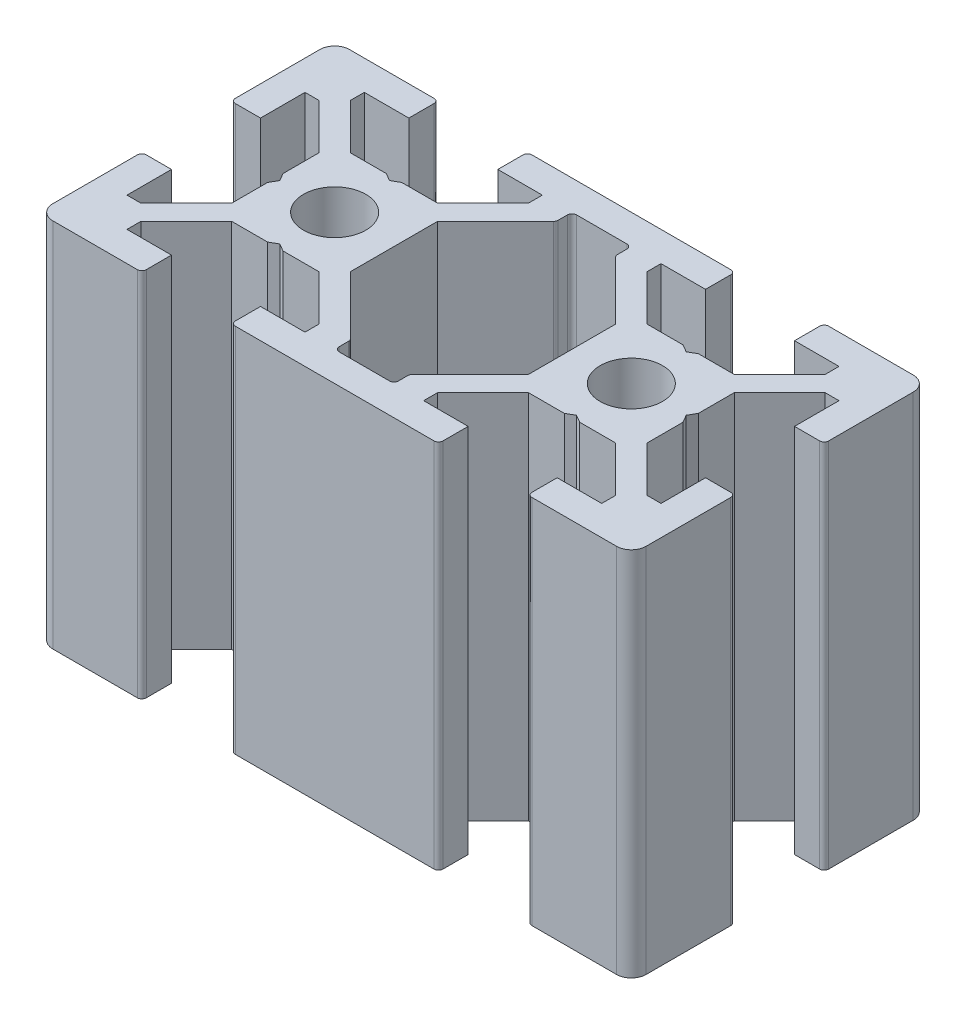
SolidWorks part; units mm, degrees
ref_plane "Front Plane" through (0, 0, 0) normal (0, 0, 1) x (1, 0, 0)
ref_plane "Top Plane" through (0, 0, 0) normal (0, 1, 0) x (1, 0, 0)
ref_plane "Right Plane" through (0, 0, 0) normal (1, 0, 0) x (0, 0, -1)
sketch "Sketch1" plane through (0, 0, 0) normal (0, 0, 1) x (1, 0, 0)
  line L0 (0, 0) -> (0, 25)
  dimension "D1" = 25
other "Structural Member1"
ref_plane "Plane1" through (0, 0, 0) normal (0, 1, 0) x (0, 0, 1)
sketch "Model" plane through (0, 0, 0) normal (0, 1, 0) x (0, 0, 1)
  line L0 (-10, -13.3) -> (-10, -19)
  line L1 (-8, -13) -> (-9.7, -13)
  line L2 (-8, -16) -> (-8, -13)
  line L3 (-7.0606, -16) -> (-8, -16)
  line L4 (-4, -12.9394) -> (-7.0606, -16)
  line L5 (-4, -10.5196) -> (-4, -12.9394)
  line L6 (-3.7, -10) -> (-4, -10.5196)
  line L7 (-4, -9.4804) -> (-3.7, -10)
  line L8 (-4, -7.0607) -> (-4, -9.4804)
  line L9 (-7.0607, -4) -> (-4, -7.0607)
  line L10 (-8, -4) -> (-7.0607, -4)
  line L11 (-8, -7) -> (-8, -4)
  line L12 (-9.7, -7) -> (-8, -7)
  line L13 (-10, 6.7) -> (-10, -6.7)
  line L14 (-8, 7) -> (-9.7, 7)
  line L15 (-8, 4) -> (-8, 7)
  line L16 (-7.0607, 4) -> (-8, 4)
  line L17 (-4, 7.0607) -> (-7.0607, 4)
  line L18 (-4, 9.4804) -> (-4, 7.0607)
  line L19 (-3.7, 10) -> (-4, 9.4804)
  line L20 (-4, 10.5196) -> (-3.7, 10)
  line L21 (-4, 12.9394) -> (-4, 10.5196)
  line L22 (-7.0606, 16) -> (-4, 12.9394)
  line L23 (-8, 16) -> (-7.0606, 16)
  line L24 (-8, 13) -> (-8, 16)
  line L25 (-9.7, 13) -> (-8, 13)
  line L26 (-10, 19) -> (-10, 13.3)
  line L27 (-3.3, 20) -> (-9, 20)
  line L28 (-3, 18) -> (-3, 19.7)
  line L29 (-6, 18) -> (-3, 18)
  line L30 (-6, 17.0607) -> (-6, 18)
  line L31 (-2.9393, 14) -> (-6, 17.0607)
  line L32 (-0.5196, 14) -> (-2.9393, 14)
  line L33 (0, 13.7) -> (-0.5196, 14)
  line L34 (0.5196, 14) -> (0, 13.7)
  line L35 (2.9394, 14) -> (0.5196, 14)
  line L36 (6, 17.0607) -> (2.9394, 14)
  line L37 (6, 18) -> (6, 17.0607)
  line L38 (3, 18) -> (6, 18)
  line L39 (3, 19.7) -> (3, 18)
  line L40 (9, 20) -> (3.3, 20)
  line L41 (10, 13.3) -> (10, 19)
  line L42 (8, 13) -> (9.7, 13)
  line L43 (8, 16) -> (8, 13)
  line L44 (7.0607, 16) -> (8, 16)
  line L45 (4, 12.9393) -> (7.0607, 16)
  line L46 (4, 10.5196) -> (4, 12.9393)
  line L47 (3.7, 10) -> (4, 10.5196)
  line L48 (4, 9.4804) -> (3.7, 10)
  line L49 (4, 7.0607) -> (4, 9.4804)
  line L50 (7.0607, 4) -> (4, 7.0607)
  line L51 (8, 4) -> (7.0607, 4)
  line L52 (8, 7) -> (8, 4)
  line L53 (9.7, 7) -> (8, 7)
  line L54 (10, -6.7) -> (10, 6.7)
  line L55 (8, -7) -> (9.7, -7)
  line L56 (8, -4) -> (8, -7)
  line L57 (7.0607, -4) -> (8, -4)
  line L58 (4, -7.0607) -> (7.0607, -4)
  line L59 (4, -9.4804) -> (4, -7.0607)
  line L60 (3.7, -10) -> (4, -9.4804)
  line L61 (4, -10.5196) -> (3.7, -10)
  line L62 (4, -12.9393) -> (4, -10.5196)
  line L63 (7.0607, -16) -> (4, -12.9393)
  line L64 (8, -16) -> (7.0607, -16)
  line L65 (8, -13) -> (8, -16)
  line L66 (9.7, -13) -> (8, -13)
  line L67 (10, -19) -> (10, -13.3)
  line L68 (3.3, -20) -> (9, -20)
  line L69 (3, -18) -> (3, -19.7)
  line L70 (6, -18) -> (3, -18)
  line L71 (6, -17.0607) -> (6, -18)
  line L72 (2.9393, -14) -> (6, -17.0607)
  line L73 (0.5196, -14) -> (2.9393, -14)
  line L74 (0, -13.7) -> (0.5196, -14)
  line L75 (-0.5196, -14) -> (0, -13.7)
  line L76 (-2.9393, -14) -> (-0.5196, -14)
  line L77 (-6, -17.0607) -> (-2.9393, -14)
  line L78 (-6, -18) -> (-6, -17.0607)
  line L79 (-3, -18) -> (-6, -18)
  line L80 (-3, -19.7) -> (-3, -18)
  line L81 (-9, -20) -> (-3.3, -20)
  line L82 (-8, 1.7) -> (-8, -1.7)
  line L83 (-7.7, -2) -> (-7.0636, -2)
  line L84 (-6.8515, -2.0879) -> (-2.9393, -6)
  line L85 (-2.9393, -6) -> (2.9393, -6)
  line L86 (2.9393, -6) -> (6.8515, -2.0879)
  line L87 (7.0636, -2) -> (7.7, -2)
  line L88 (8, -1.7) -> (8, 1.7)
  line L89 (7.7, 2) -> (7.0636, 2)
  line L90 (6.8515, 2.0879) -> (2.9393, 6)
  line L91 (2.9393, 6) -> (-2.9393, 6)
  line L92 (-2.9393, 6) -> (-6.8515, 2.0879)
  line L93 (-7.0636, 2) -> (-7.7, 2)
  line L94 (-2.5472, 10) -> (2.5472, 10) construction
  line L95 (0, 7.4528) -> (0, 12.5472) construction
  line L96 (-2.5472, -10) -> (2.5472, -10) construction
  line L97 (0, -12.5472) -> (0, -7.4528) construction
  line L98 (-10.4472, -13.3) -> (-8.9528, -13.3) construction
  line L99 (-9.7, -14.0472) -> (-9.7, -12.5528) construction
  line L100 (-10.4472, -6.7) -> (-8.9528, -6.7) construction
  line L101 (-9.7, -7.4472) -> (-9.7, -5.9528) construction
  line L102 (-10.4472, 6.7) -> (-8.9528, 6.7) construction
  line L103 (-9.7, 5.9528) -> (-9.7, 7.4472) construction
  line L104 (-10.4472, 13.3) -> (-8.9528, 13.3) construction
  line L105 (-9.7, 12.5528) -> (-9.7, 14.0472) construction
  line L106 (-4.0472, 19.7) -> (-2.5528, 19.7) construction
  line L107 (-3.3, 18.9528) -> (-3.3, 20.4472) construction
  line L108 (2.5528, 19.7) -> (4.0472, 19.7) construction
  line L109 (3.3, 18.9528) -> (3.3, 20.4472) construction
  line L110 (8.9528, 13.3) -> (10.4472, 13.3) construction
  line L111 (9.7, 12.5528) -> (9.7, 14.0472) construction
  line L112 (8.9528, 6.7) -> (10.4472, 6.7) construction
  line L113 (9.7, 5.9528) -> (9.7, 7.4472) construction
  line L114 (8.9528, -6.7) -> (10.4472, -6.7) construction
  line L115 (9.7, -7.4472) -> (9.7, -5.9528) construction
  line L116 (8.9528, -13.3) -> (10.4472, -13.3) construction
  line L117 (9.7, -14.0472) -> (9.7, -12.5528) construction
  line L118 (2.5528, -19.7) -> (4.0472, -19.7) construction
  line L119 (3.3, -20.4472) -> (3.3, -18.9528) construction
  line L120 (-4.0472, -19.7) -> (-2.5528, -19.7) construction
  line L121 (-3.3, -20.4472) -> (-3.3, -18.9528) construction
  line L122 (-8.4472, 1.7) -> (-6.9528, 1.7) construction
  line L123 (-7.7, 0.9528) -> (-7.7, 2.4472) construction
  line L124 (-8.4472, -1.7) -> (-6.9528, -1.7) construction
  line L125 (-7.7, -2.4472) -> (-7.7, -0.9528) construction
  line L126 (6.9528, -1.7) -> (8.4472, -1.7) construction
  line L127 (7.7, -2.4472) -> (7.7, -0.9528) construction
  line L128 (6.9528, 1.7) -> (8.4472, 1.7) construction
  line L129 (7.7, 0.9528) -> (7.7, 2.4472) construction
  arc A0 (-9.7, -13) -> (-10, -13.3) centre (-9.7, -13.3) ccw
  arc A1 (-10, -6.7) -> (-9.7, -7) centre (-9.7, -6.7) ccw
  arc A2 (-9.7, 7) -> (-10, 6.7) centre (-9.7, 6.7) ccw
  arc A3 (-10, 13.3) -> (-9.7, 13) centre (-9.7, 13.3) ccw
  arc A4 (-9, 20) -> (-10, 19) centre (-9, 19) ccw
  arc A5 (-3, 19.7) -> (-3.3, 20) centre (-3.3, 19.7) ccw
  arc A6 (3.3, 20) -> (3, 19.7) centre (3.3, 19.7) ccw
  arc A7 (10, 19) -> (9, 20) centre (9, 19) ccw
  arc A8 (9.7, 13) -> (10, 13.3) centre (9.7, 13.3) ccw
  arc A9 (10, 6.7) -> (9.7, 7) centre (9.7, 6.7) ccw
  arc A10 (9.7, -7) -> (10, -6.7) centre (9.7, -6.7) ccw
  arc A11 (10, -13.3) -> (9.7, -13) centre (9.7, -13.3) ccw
  arc A12 (9, -20) -> (10, -19) centre (9, -19) ccw
  arc A13 (3, -19.7) -> (3.3, -20) centre (3.3, -19.7) ccw
  arc A14 (-3.3, -20) -> (-3, -19.7) centre (-3.3, -19.7) ccw
  arc A15 (-10, -19) -> (-9, -20) centre (-9, -19) ccw
  circle A16 centre (0, 10) radius 2.1
  circle A17 centre (0, -10) radius 2.1
  arc A18 (-7.7, 2) -> (-8, 1.7) centre (-7.7, 1.7) ccw
  arc A19 (-8, -1.7) -> (-7.7, -2) centre (-7.7, -1.7) ccw
  arc A20 (-6.8515, -2.0879) -> (-7.0636, -2) centre (-7.0635, -2.2999) ccw
  arc A21 (7.0636, -2) -> (6.8515, -2.0879) centre (7.0635, -2.2999) ccw
  arc A22 (7.7, -2) -> (8, -1.7) centre (7.7, -1.7) ccw
  arc A23 (8, 1.7) -> (7.7, 2) centre (7.7, 1.7) ccw
  arc A24 (6.8515, 2.0879) -> (7.0636, 2) centre (7.0635, 2.2999) ccw
  arc A25 (-7.0636, 2) -> (-6.8515, 2.0879) centre (-7.0635, 2.2998) ccw
  point P218 (0, 0)
  point P219 (0, 0)
